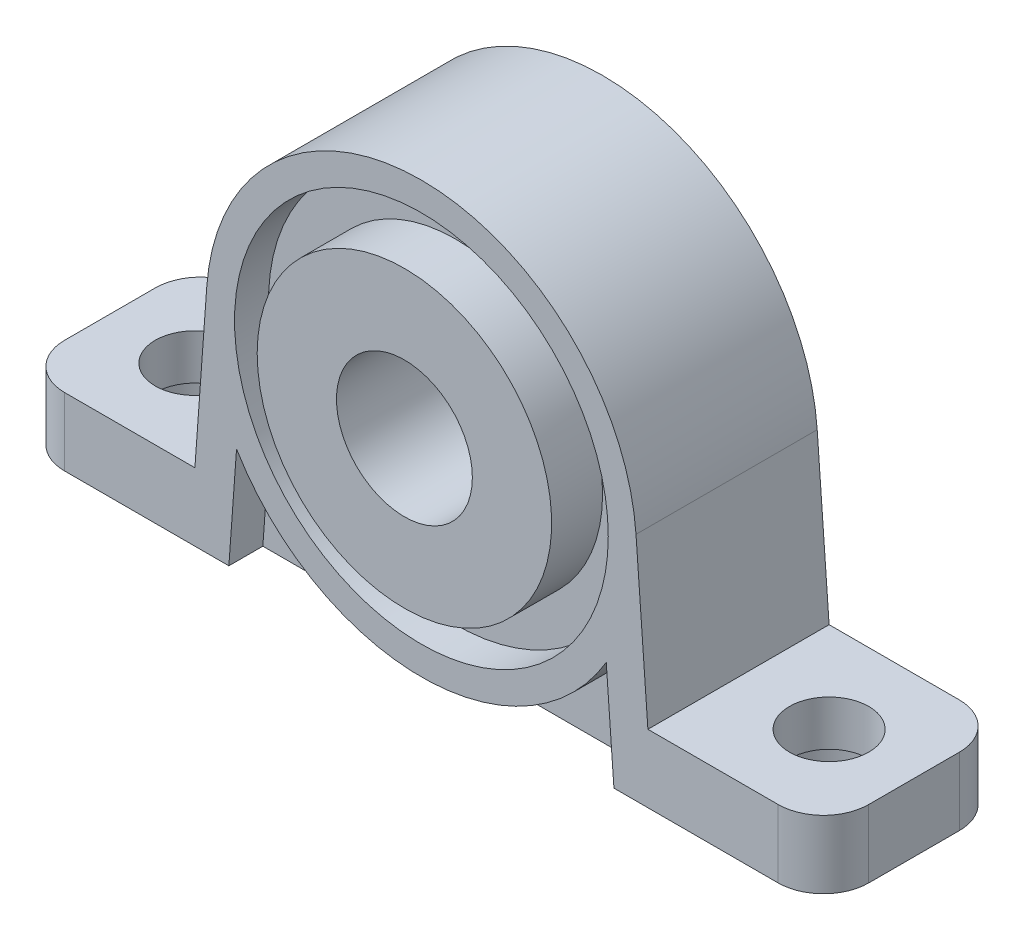
SolidWorks part; units mm, degrees
material "锌合金 7; AG40B; Zn-4Al-0.015Mg"
ref_plane "前视基准面" through (0, 0, 0) normal (0, 0, 1) x (1, 0, 0)
ref_plane "上视基准面" through (0, 0, 0) normal (0, 1, 0) x (1, 0, 0)
ref_plane "右视基准面" through (0, 0, 0) normal (1, 0, 0) x (0, 0, -1)
sketch "草图1" plane through (0, 0, 0) normal (0, 0, 1) x (1, 0, 0)
  line L0 (-18.9495, 17.3839) -> (-20, 3)
  line L1 (-35.5, -3) -> (35.5, -3)
  line L2 (-35.5, -3) -> (-35.5, 3)
  line L3 (-35.5, 3) -> (35.5, 3)
  line L4 (35.5, -3) -> (35.5, 3)
  line L5 (-35.5, -3) -> (35.5, 3) construction
  line L6 (-35.5, 3) -> (35.5, -3) construction
  line L7 (18.9495, 17.3839) -> (20, 3)
  line L8 (0, 0) -> (0, 12.3208) construction
  line L9 (-17, -3) -> (-16.3226, 6.2752)
  line L10 (17, -3) -> (16.3226, 6.2752)
  circle A0 centre (0, 16) radius 19
  point P0 (0, 0)
  dimension "D1" = 6
  dimension "D3" = 38
  dimension "D2" = 71
  dimension "D4" = 19
  dimension "D5" = 40
  dimension "D6" = 34
extrude "凸台-拉伸1" add sketch "草图1" along normal mid plane 16
sketch "草图3" plane through (0, 0, 0) normal (0, 0, 1) x (1, 0, 0)
  line L0 (-17, -3) -> (17, -3)
  line L10 (16.3226, 6.2752) -> (17, -3)
  line L11 (17, -3) -> (35.5, -3)
  line L12 (35.5, -3) -> (35.5, 3)
  line L13 (35.5, 3) -> (20, 3)
  line L14 (20, 3) -> (18.9495, 17.3839)
  line L15 (-18.9495, 17.3839) -> (-20, 3)
  line L16 (-20, 3) -> (-35.5, 3)
  line L17 (-35.5, 3) -> (-35.5, -3)
  line L18 (-35.5, -3) -> (-17, -3)
  line L19 (-17, -3) -> (-16.3226, 6.2752)
  line L20 (16.3226, 6.2752) -> (17, -3)
  line L21 (17, -3) -> (35.5, -3)
  line L22 (35.5, -3) -> (35.5, 3)
  line L23 (35.5, 3) -> (20, 3)
  line L24 (20, 3) -> (18.9495, 17.3839)
  line L25 (-18.9495, 17.3839) -> (-20, 3)
  line L26 (-20, 3) -> (-35.5, 3)
  line L27 (-35.5, 3) -> (-35.5, -3)
  line L28 (-35.5, -3) -> (-17, -3)
  line L29 (-17, -3) -> (-16.3226, 6.2752)
  arc A2 (-16.3226, 6.2752) -> (16.3226, 6.2752) centre (0, 16) ccw
  arc A3 (18.9495, 17.3839) -> (-18.9495, 17.3839) centre (0, 16) ccw
  arc A4 (-16.3226, 6.2752) -> (16.3226, 6.2752) centre (0, 16) ccw
  arc A5 (18.9495, 17.3839) -> (-18.9495, 17.3839) centre (0, 16) ccw
  dimension "D1" = 0
extrude "凸台-拉伸2" add sketch "草图3" along normal mid plane 10 contours A4 L29 L0 | A4 L0 L20
sketch "草图4" plane through (0, 0, 8) normal (0, 0, 1) x (1, 0, 0)
  circle A0 centre (0, 16) radius 16.5
  dimension "D1" = 33
extrude "切除-拉伸1" cut sketch "草图4" against normal blind 3
mirror "镜向1" about plane through (0, 0, 0) normal (0, 0, 1) of "切除-拉伸1"
sketch "草图5" plane through (0, 0, 5) normal (0, 0, 1) x (1, 0, 0)
  circle A0 centre (0, 16) radius 13
  dimension "D1" = 26
extrude "凸台-拉伸3" add sketch "草图5" along normal offset from surface (4.5 mm away) 14.5 up to face at (16.5, 16, -5)
sketch "草图6" plane through (0, 0, 9.5) normal (0, 0, 1) x (1, 0, 0)
  circle A0 centre (0, 16) radius 6
  dimension "D1" = 12
extrude "切除-拉伸3" cut sketch "草图6" against normal through all
fillet "圆角1" radius 4 4 edges at (35.5, 0, -8) (35.5, 0, 8) (-35.5, 0, -8) (-35.5, 0, 8)
sketch "草图7" plane through (0, -3, 0) normal (0, -1, 0) x (1, 0, 0)
  circle A0 centre (-28, 0) radius 5
  dimension "D1" = 10
  dimension "D2" = 28
extrude "切除-拉伸4" cut sketch "草图7" against normal blind 2
sketch "草图8" plane through (0, -1, 0) normal (0, -1, 0) x (1, 0, 0)
  circle A0 centre (-28, 0) radius 3.5
  dimension "D1" = 7
extrude "切除-拉伸5" cut sketch "草图8" against normal up to next
mirror "镜向2" about plane through (0, 0, 0) normal (1, 0, 0) of "切除-拉伸4", "切除-拉伸5"
